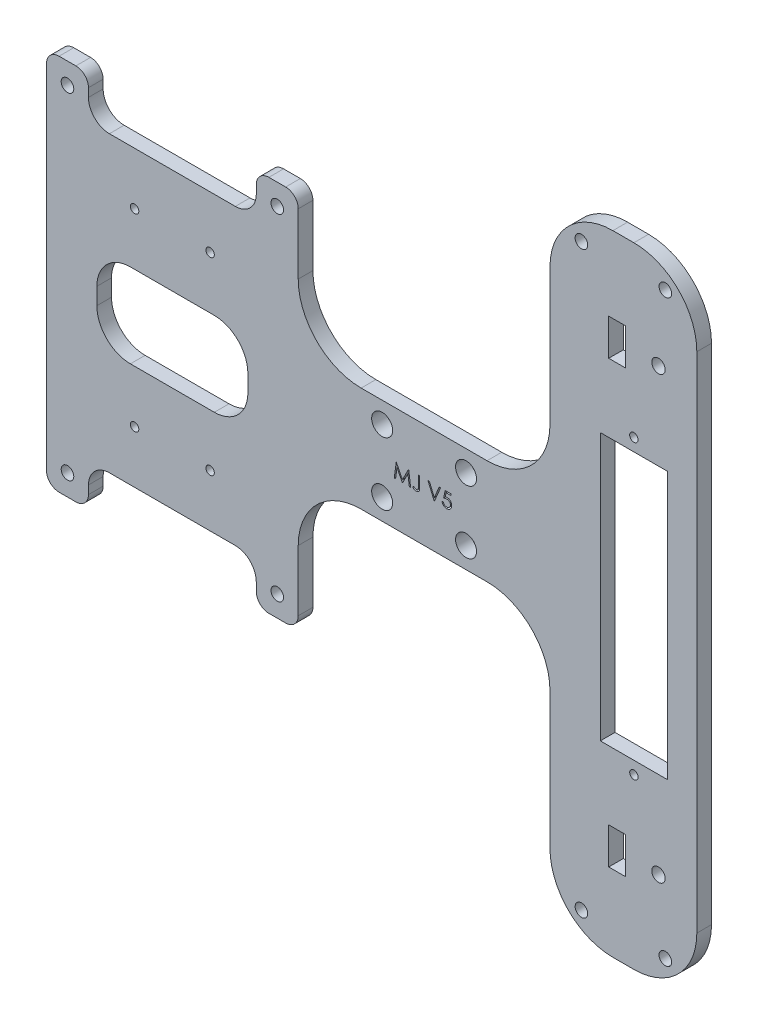
SolidWorks part; units mm, degrees
material "ABS"
ref_plane "Plano frontal" through (0, 0, 0) normal (0, 0, 1) x (1, 0, 0)
ref_plane "Plano superior" through (0, 0, 0) normal (0, 1, 0) x (1, 0, 0)
ref_plane "Plano direito" through (0, 0, 0) normal (1, 0, 0) x (0, 0, -1)
sketch "Esboço1" plane through (0, 0, 0) normal (0, 0, 1) x (1, 0, 0)
  line L0 (-54.9538, 26.581) -> (-14.9538, 26.581)
  line L1 (-64.9538, 26.581) -> (-64.9538, -43.419)
  line L2 (-54.9538, -43.419) -> (-14.9538, -43.419)
  line L3 (-4.9538, 26.581) -> (-4.9538, 4.081)
  line L4 (-64.9538, 26.581) -> (-64.9538, 33.581)
  line L5 (-61.9538, 36.581) -> (-57.9538, 36.581)
  line L6 (-54.9538, 26.581) -> (-54.9538, 33.581)
  line L7 (-4.9538, 26.581) -> (-4.9538, 33.581)
  line L8 (-7.9538, 36.581) -> (-11.9538, 36.581)
  line L9 (-14.9538, 26.581) -> (-14.9538, 33.581)
  line L10 (-64.9538, -43.419) -> (-64.9538, -50.419)
  line L11 (-61.9538, -53.419) -> (-57.9538, -53.419)
  line L12 (-54.9538, -43.419) -> (-54.9538, -50.419)
  line L13 (-4.9538, -43.419) -> (-4.9538, -50.419)
  line L14 (-7.9538, -53.419) -> (-11.9538, -53.419)
  line L15 (-14.9538, -43.419) -> (-14.9538, -50.419)
  line L16 (-4.9538, 4.081) -> (55.0462, 4.081)
  line L17 (-4.9538, -20.919) -> (55.0462, -20.919)
  line L18 (-4.9538, -20.919) -> (-4.9538, -43.419)
  line L19 (55.0462, 66.576) -> (90.0462, 66.576)
  line L20 (55.0462, 66.576) -> (55.0462, 4.081)
  line L21 (55.0462, -83.424) -> (90.0462, -83.424)
  line L22 (90.0462, 66.576) -> (90.0462, -83.424)
  line L23 (55.0462, -20.919) -> (55.0462, -83.424)
  arc A0 (-64.9538, 33.581) -> (-61.9538, 36.581) centre (-61.9538, 33.581) cw
  arc A1 (-57.9538, 36.581) -> (-54.9538, 33.581) centre (-57.9538, 33.581) cw
  arc A2 (-11.9538, 36.581) -> (-14.9538, 33.581) centre (-11.9538, 33.581) ccw
  arc A3 (-4.9538, 33.581) -> (-7.9538, 36.581) centre (-7.9538, 33.581) ccw
  arc A4 (-4.9538, -50.419) -> (-7.9538, -53.419) centre (-7.9538, -50.419) cw
  arc A5 (-11.9538, -53.419) -> (-14.9538, -50.419) centre (-11.9538, -50.419) cw
  arc A6 (-57.9538, -53.419) -> (-54.9538, -50.419) centre (-57.9538, -50.419) ccw
  arc A7 (-64.9538, -50.419) -> (-61.9538, -53.419) centre (-61.9538, -50.419) ccw
  dimension "D3" = 3
  dimension "D9" = 3
  dimension "D1" = 70
  dimension "D2" = 60
  dimension "D4" = 25
  dimension "D5" = 32.5
  dimension "D6" = 90
  dimension "D7" = 60
  dimension "D8" = 70
  dimension "D10" = 7
  dimension "D11" = 32.5
  dimension "D12" = 60
  dimension "D13" = 60
  dimension "D14" = 150
  dimension "D15" = 35
  dimension "D16" = 62.505
  dimension "D17" = 62.495
extrude "Ressalto-extrusão1" add sketch "Esboço1" along normal blind 3.5 contours L16 L20 L19 L22 L21 L23 L17 L18 L13 A4 L14 A5 L15 L2 L12 A6 L11 A7 L10 L1 L4 A0 L5 A1 L6 L0 L9 A2 L8 A3 L7 L3
fillet "Filete1" radius 15 8 edges at (55.0462, -20.919, 1.75) (-4.9538, -20.919, 1.75) (-4.9538, 4.081, 1.75) (55.0462, 4.081, 1.75) (55.0462, 66.576, 1.75) (90.0462, 66.576, 1.75) (55.0462, -83.424, 1.75) (90.0462, -83.424, 1.75)
fillet "Filete2" radius 5 4 edges at (-54.9538, -43.419, 1.75) (-14.9538, -43.419, 1.75) (-14.9538, 26.581, 1.75) (-54.9538, 26.581, 1.75)
sketch "Esboço2" plane through (0, 0, 3.5) normal (0, 0, 1) x (1, 0, 0)
  line L0 (-7.9538, -53.419) -> (-11.9538, -53.419) construction
  line L1 (-4.9538, -35.919) -> (-4.9538, -50.419) construction
  line L2 (-64.9538, 33.581) -> (-64.9538, -50.419) construction
  line L3 (-61.9538, -53.419) -> (-57.9538, -53.419) construction
  line L4 (-49.9538, -43.419) -> (-19.9538, -43.419) construction
  line L5 (-64.9538, -8.419) -> (-43.9549, -8.419) construction
  circle A0 centre (-25.9538, -30.919) radius 1
  circle A1 centre (-43.9538, -30.919) radius 1
  circle A2 centre (-59.9538, 31.581) radius 1.5
  circle A3 centre (-9.9538, 31.581) radius 1.5
  circle A4 centre (-9.9538, -48.419) radius 1.5
  circle A5 centre (-59.9538, -48.419) radius 1.5
  circle A6 centre (-43.9538, 14.081) radius 1
  circle A7 centre (-25.9538, 14.081) radius 1
  dimension "D1" = 18
  dimension "D2" = 2
  dimension "D3" = 2
  dimension "D4" = 21
  dimension "D5" = 12.5
  dimension "D6" = 3
  dimension "D7" = 3
  dimension "D9" = 5
  dimension "D10" = 5
  dimension "D11" = 5
  dimension "D12" = 12.5
  dimension "D13" = 21
  dimension "D8" = 5
extrude "Corte-extrusão1" cut sketch "Esboço2" against normal blind 12.42
sketch "Esboço3" plane through (0, 0, 3.5) normal (0, 0, 1) x (1, 0, 0)
  line L0 (-49.9538, -43.419) -> (-19.9538, -43.419) construction
  line L1 (-24.9538, -18.419) -> (-44.9538, -18.419)
  line L2 (-16.9538, -10.419) -> (-16.9538, -6.419)
  line L3 (-24.9538, 1.581) -> (-44.9538, 1.581)
  line L4 (-52.9538, -10.419) -> (-52.9538, -6.419)
  line L5 (-49.9538, 26.581) -> (-19.9538, 26.581) construction
  line L6 (-64.9538, 33.581) -> (-64.9538, -50.419) construction
  line L7 (-4.9538, 33.581) -> (-4.9538, 19.081) construction
  arc A0 (-44.9538, 1.581) -> (-52.9538, -6.419) centre (-44.9538, -6.419) ccw
  arc A1 (-44.9538, -18.419) -> (-52.9538, -10.419) centre (-44.9538, -10.419) cw
  arc A2 (-24.9538, -18.419) -> (-16.9538, -10.419) centre (-24.9538, -10.419) ccw
  arc A3 (-16.9538, -6.419) -> (-24.9538, 1.581) centre (-24.9538, -6.419) ccw
  dimension "D5" = 8
  dimension "D1" = 25
  dimension "D2" = 25
  dimension "D3" = 12
  dimension "D4" = 12
extrude "Corte-extrusão2" cut sketch "Esboço3" against normal blind 3.5
sketch "Esboço5" plane through (0, 0, 3.5) normal (0, 0, 1) x (1, 0, 0)
  line L0 (90.0462, 51.576) -> (90.0462, -68.424) construction
  line L2 (70.0462, -83.424) -> (75.0462, -83.424) construction
  line L3 (70.0462, 66.576) -> (75.0462, 66.576) construction
  line L4 (73.0462, 48.426) -> (69.0462, 48.426)
  line L5 (73.0462, 48.426) -> (73.0462, 39.726)
  line L6 (73.0462, 39.726) -> (69.0462, 39.726)
  line L7 (69.0462, 48.426) -> (69.0462, 39.726)
  line L8 (73.0462, -56.574) -> (69.0462, -56.574)
  line L9 (73.0462, -56.574) -> (73.0462, -65.274)
  line L10 (73.0462, -65.274) -> (69.0462, -65.274)
  line L11 (69.0462, -56.574) -> (69.0462, -65.274)
  line L12 (83.0462, 23.396) -> (67.0462, 23.396)
  line L13 (83.0462, 23.396) -> (83.0462, -40.244)
  line L14 (83.0462, -40.244) -> (67.0462, -40.244)
  line L15 (67.0462, 23.396) -> (67.0462, -40.244)
  circle A0 centre (80.9062, 44.076) radius 1.6
  circle A1 centre (80.9062, -60.924) radius 1.6
  circle A2 centre (75.0462, 26.396) radius 1
  circle A3 centre (75.0462, -43.244) radius 1
  point P20 (75.0462, 23.396)
  point P24 (72.5462, -83.424)
  dimension "D1" = 105
  dimension "D2" = 9.14
  dimension "D3" = 9.14
  dimension "D4" = 3.2
  dimension "D5" = 3.2
  dimension "D6" = 22.5
  dimension "D10" = 4.35
  dimension "D20" = 3
  dimension "D21" = 8
  dimension "D22" = 2
  dimension "D23" = 3
  dimension "D24" = 8
  dimension "D25" = 2
  dimension "D7" = 8.7
  dimension "D8" = 7.86
  dimension "D9" = 4
  dimension "D11" = 8.7
  dimension "D12" = 7.86
  dimension "D13" = 4
  dimension "D14" = 4.35
  dimension "D15" = 63.64
  dimension "D16" = 16
  dimension "D17" = 7
  dimension "D18" = 43.18
  dimension "D19" = 43.18
extrude "Corte-extrusão3" cut sketch "Esboço5" against normal blind 3.5
sketch "Esboço6" plane through (0, 0, 3.5) normal (0, 0, 1) x (1, 0, 0)
  line L0 (70.0462, 66.576) -> (75.0462, 66.576) construction
  line L2 (90.0462, 51.576) -> (90.0462, -68.424) construction
  line L3 (90.0462, -8.424) -> (75.6707, -8.424) construction
  circle A0 centre (82.5462, 60.576) radius 1.5
  circle A1 centre (62.5462, 60.576) radius 1.5
  circle A2 centre (62.5462, -77.424) radius 1.5
  circle A3 centre (82.5462, -77.424) radius 1.5
  point P6 (72.5462, 66.576)
  dimension "D1" = 20
  dimension "D2" = 6
  dimension "D3" = 7.5
  dimension "D4" = 3
  dimension "D5" = 3
  dimension "D6" = 6
extrude "Corte-extrusão4" cut sketch "Esboço6" against normal blind 3.5
sketch "Esboço7" plane through (0, 0, 3.5) normal (0, 0, 1) x (1, 0, 0)
  line L0 (10.0462, 4.081) -> (40.0462, 4.081) construction
  line L1 (55.0462, 51.576) -> (55.0462, 19.081) construction
  line L2 (55.0462, -35.919) -> (55.0462, -68.424) construction
  line L3 (10.0462, -20.919) -> (40.0462, -20.919) construction
  line L4 (-4.9538, -35.919) -> (-4.9538, -50.419) construction
  line L5 (-4.9538, 33.581) -> (-4.9538, 19.081) construction
  circle A0 centre (35.0462, -0.919) radius 2.5
  circle A1 centre (35.0462, -15.919) radius 2.5
  circle A2 centre (15.0462, -0.919) radius 2.5
  circle A3 centre (15.0462, -15.919) radius 2.5
  dimension "D1" = 5
  dimension "D2" = 5
  dimension "D4" = 20
  dimension "D5" = 5
  dimension "D6" = 5
  dimension "D7" = 5
  dimension "D8" = 20
  dimension "D9" = 5
  dimension "D10" = 20
  dimension "D11" = 5
  dimension "D12" = 5
  dimension "D3" = 20
extrude "Corte-extrusão5" cut sketch "Esboço7" against normal blind 7
sketch "Esboço8" plane through (0, 0, 3.5) normal (0, 0, 1) x (1, 0, 0)
  text T0 "MJ V5"
extrude "Corte-extrusão6" cut sketch "Esboço8" against normal blind 7
